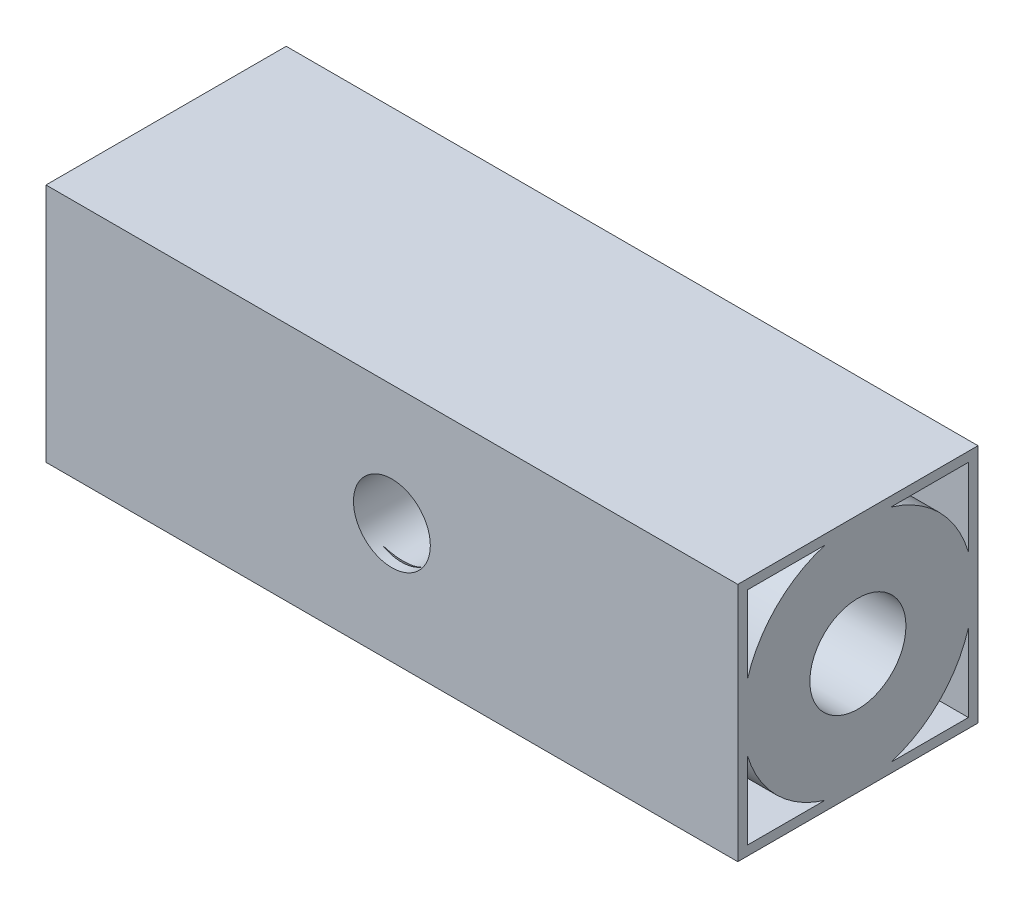
SolidWorks part; units mm, degrees
ref_plane "Front Plane" through (0, 0, 0) normal (0, 0, 1) x (1, 0, 0)
ref_plane "Top Plane" through (0, 0, 0) normal (0, 1, 0) x (1, 0, 0)
ref_plane "Right Plane" through (0, 0, 0) normal (1, 0, 0) x (0, 0, -1)
sketch "Sketch1" plane through (0, 0, 0) normal (1, 0, 0) x (0, 0, -1)
  line L0 (-12.5, 12.5) -> (12.5, 12.5)
  line L1 (-11.5, -11.5) -> (-3.4278, -11.5)
  line L2 (-11.5, -11.5) -> (-11.5, -3.4278)
  line L3 (-11.5, 11.5) -> (-3.4278, 11.5)
  line L4 (11.5, -11.5) -> (11.5, -3.4278)
  line L5 (-11.5, -11.5) -> (11.5, 11.5) construction
  line L6 (-11.5, 11.5) -> (11.5, -11.5) construction
  line L7 (12.5, -12.5) -> (12.5, 12.5)
  line L8 (-12.5, -12.5) -> (12.5, -12.5)
  line L9 (-12.5, -12.5) -> (-12.5, 12.5)
  line L10 (3.4278, 11.5) -> (11.5, 11.5)
  line L11 (-11.5, 3.4278) -> (-11.5, 11.5)
  line L12 (-11.5, 11.5) -> (11.5, 11.5) construction
  line L13 (3.4278, -11.5) -> (11.5, -11.5)
  line L14 (-11.5, -11.5) -> (-11.5, 11.5) construction
  line L15 (11.5, 3.4278) -> (11.5, 11.5)
  line L16 (-11.5, -11.5) -> (11.5, -11.5) construction
  line L18 (11.5, -11.5) -> (11.5, 11.5) construction
  arc A0 (-3.4278, 11.5) -> (-11.5, 3.4278) centre (0, 0) ccw
  circle A1 centre (0, 0) radius 5
  arc A2 (-11.5, -3.4278) -> (-3.4278, -11.5) centre (0, 0) ccw
  arc A3 (3.4278, -11.5) -> (11.5, -3.4278) centre (0, 0) ccw
  arc A4 (11.5, 3.4278) -> (3.4278, 11.5) centre (0, 0) ccw
  point P0 (0, 0)
  dimension "D3" = 24
  dimension "D4" = 10
  dimension "D2" = 25
  dimension "D1" = 1
extrude "Boss-Extrude1" add sketch "Sketch1" along normal blind 72
sketch "Sketch2" plane through (0, 0, 12.5) normal (0, 0, 1) x (1, 0, 0)
  line L0 (0, 0) -> (72, 0) construction
  line L1 (72, 12.5) -> (72, -12.5) construction
  circle A0 centre (36, 0) radius 4
  dimension "D1" = 8
extrude "Cut-Extrude1" cut sketch "Sketch2" against normal through all
